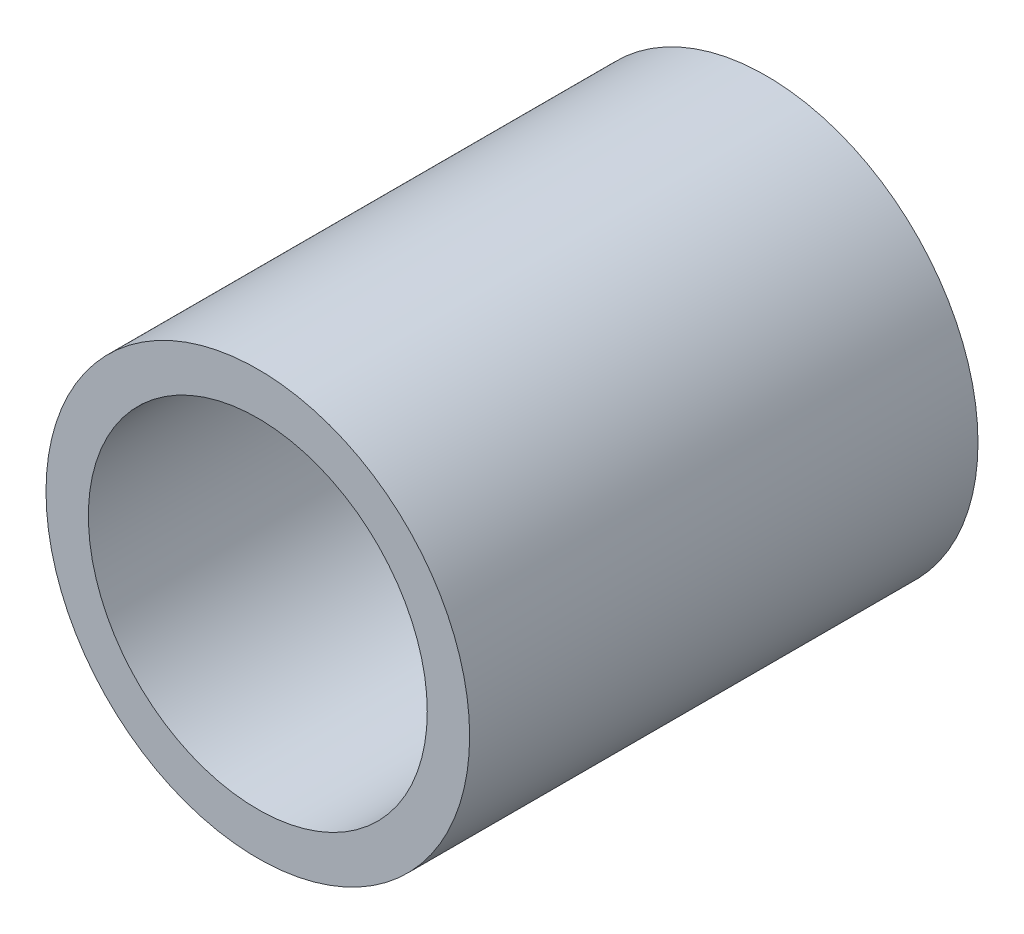
SolidWorks part; units mm, degrees
ref_plane "前视基准面" through (0, 0, 0) normal (0, 0, 1) x (1, 0, 0)
ref_plane "上视基准面" through (0, 0, 0) normal (0, 1, 0) x (1, 0, 0)
ref_plane "右视基准面" through (0, 0, 0) normal (1, 0, 0) x (0, 0, -1)
sketch "草图1" plane through (0, 0, 0) normal (0, 0, 1) x (1, 0, 0)
  circle A0 centre (0, 0) radius 10
  circle A1 centre (0, 0) radius 12.5
  dimension "D1" = 20
  dimension "D2" = 25
extrude "凸台-拉伸1" add sketch "草图1" along normal mid plane 30
